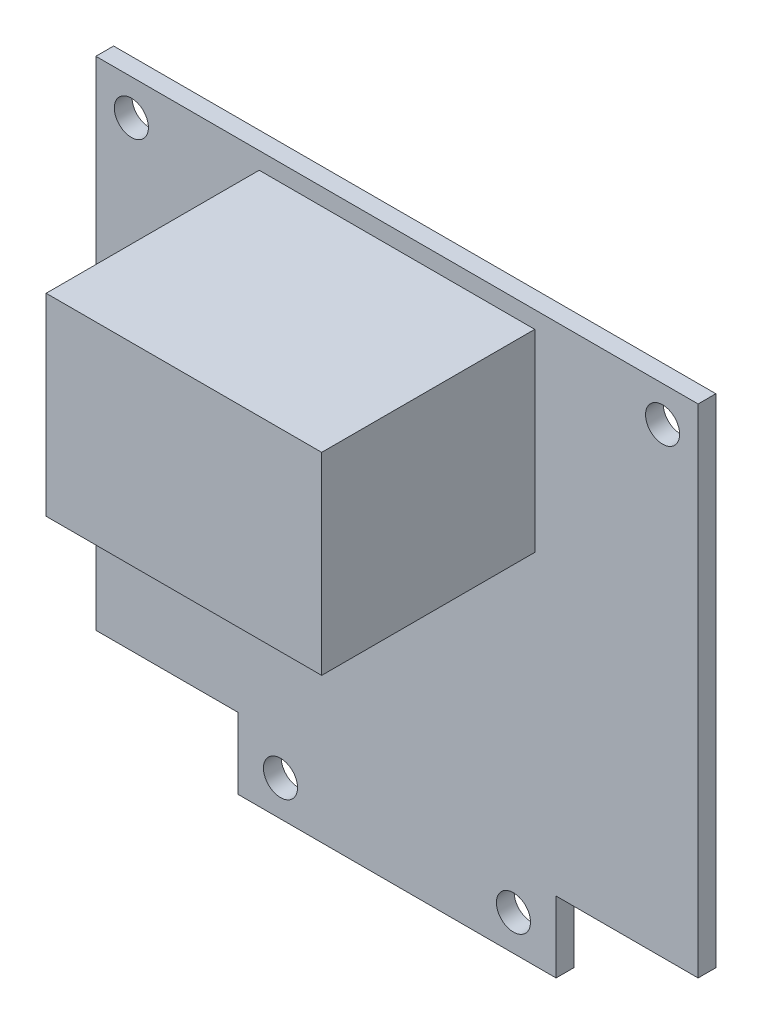
SolidWorks part; units mm, degrees
ref_plane "Front Plane" through (0, 0, 0) normal (0, 0, 1) x (1, 0, 0)
ref_plane "Top Plane" through (0, 0, 0) normal (0, 1, 0) x (1, 0, 0)
ref_plane "Right Plane" through (0, 0, 0) normal (1, 0, 0) x (0, 0, -1)
sketch "Sketch1" plane through (0, 0, 0) normal (0, 0, 1) x (1, 0, 0)
  line L0 (-26.924, -19.05) -> (-14.224, -19.05)
  line L1 (-26.924, -25.4) -> (26.924, -25.4)
  line L2 (-26.924, -25.4) -> (-26.924, 25.4)
  line L3 (-26.924, 25.4) -> (26.924, 25.4)
  line L4 (26.924, -25.4) -> (26.924, 25.4)
  line L5 (-26.924, -25.4) -> (26.924, 25.4) construction
  line L6 (-26.924, 25.4) -> (26.924, -25.4) construction
  line L7 (-14.224, -19.05) -> (-14.224, -25.4)
  line L8 (26.924, -19.05) -> (14.224, -19.05)
  line L9 (14.224, -19.05) -> (14.224, -25.4)
  circle A0 centre (-23.749, 22.225) radius 1.524
  circle A1 centre (23.749, 22.225) radius 1.524
  circle A2 centre (10.414, -22.225) radius 1.524
  circle A3 centre (-10.414, -22.225) radius 1.524
  point P0 (0, 0)
  dimension "D9" = 3.048
  dimension "D10" = 3.175
  dimension "D11" = 3.175
  dimension "D5" = 44.45
  dimension "D6" = 44.45
  dimension "D1" = 50.8
  dimension "D2" = 53.848
  dimension "D3" = 3.175
  dimension "D4" = 3.175
  dimension "D7" = 16.51
  dimension "D8" = 16.51
  dimension "D12" = 12.7
  dimension "D13" = 12.7
  dimension "D14" = 6.35
  dimension "D15" = 6.35
extrude "Boss-Extrude1" add sketch "Sketch1" along normal blind 1.5875 contours L9 L8 L4 L3 L2 L0 L7 L1 A3 A2 A1 A0
sketch "Sketch2" plane through (0, 0, 1.5875) normal (0, 0, 1) x (1, 0, 0)
  line L0 (-26.924, 25.4) -> (26.924, 25.4) construction
  line L1 (-12.319, 23.876) -> (12.319, 23.876)
  line L2 (-12.319, 23.876) -> (-12.319, 6.604)
  line L3 (-12.319, 6.604) -> (12.319, 6.604)
  line L4 (12.319, 23.876) -> (12.319, 6.604)
  dimension "D1" = 24.638
  dimension "D2" = 12.319
  dimension "D3" = 17.272
  dimension "D4" = 1.524
extrude "Boss-Extrude2" add sketch "Sketch2" along normal blind 19.05
